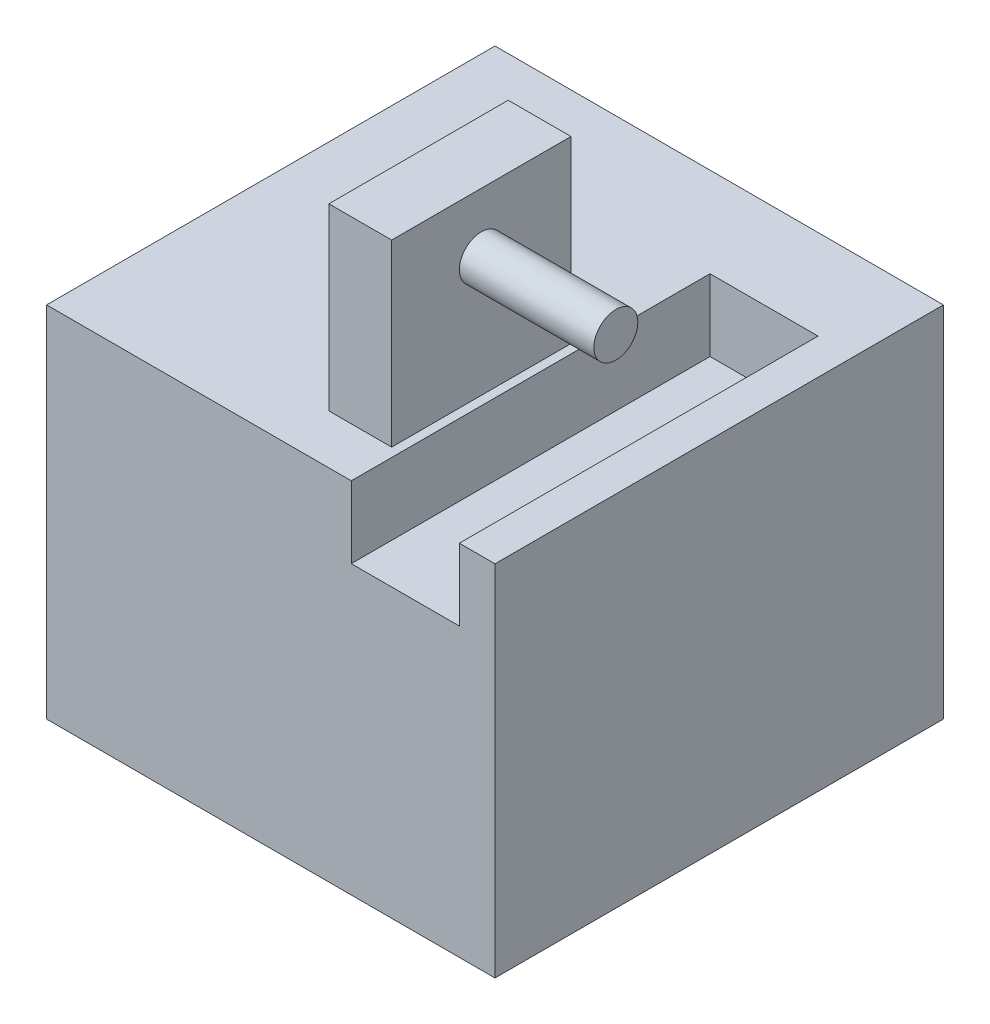
SolidWorks part; units mm, degrees
ref_plane "Front Plane" through (0, 0, 0) normal (0, 0, 1) x (1, 0, 0)
ref_plane "Top Plane" through (0, 0, 0) normal (0, 1, 0) x (1, 0, 0)
ref_plane "Right Plane" through (0, 0, 0) normal (1, 0, 0) x (0, 0, -1)
sketch "Sketch1" plane through (0, 0, 0) normal (0, 1, 0) x (1, 0, 0)
  line L1 (-40, 40) -> (40, 40)
  line L2 (-40, 40) -> (-40, -40)
  line L3 (-40, -40) -> (40, -40)
  line L4 (40, 40) -> (40, -40)
  line L5 (-40, 40) -> (40, -40) construction
  line L6 (-40, -40) -> (40, 40) construction
  point P0 (0, 0)
  dimension "D1" = 80
extrude "Boss-Extrude1" add sketch "Sketch1" along normal blind 40
sketch "Sketch2" plane through (0, 40, 0) normal (0, 1, 0) x (1, 0, 0)
  line L0 (-40, -40) -> (40, -40) construction
  line L1 (-6.025, -40) -> (6.025, -40)
  line L2 (-6.025, -40) -> (-6.025, 40)
  line L3 (-6.025, 40) -> (6.025, 40)
  line L4 (6.025, -40) -> (6.025, 40)
  line L5 (40, 40) -> (-40, 40) construction
  point P7 (0, 40)
  dimension "D1" = 12.05
extrude "Cut-Extrude1" cut sketch "Sketch2" against normal blind 8
sketch "Sketch3" plane through (0, 40, 0) normal (0, 1, 0) x (1, 0, 0)
  line L1 (-7.025, -14.5) -> (-14.025, -14.5)
  line L2 (-7.025, -14.5) -> (-7.025, -34.5)
  line L3 (-7.025, -34.5) -> (-14.025, -34.5)
  line L4 (-14.025, -14.5) -> (-14.025, -34.5)
  line L7 (-6.025, 40) -> (-6.025, -40) construction
  dimension "D1" = 20
  dimension "D2" = 7
  dimension "D3" = 14.5
  dimension "D4" = 1
extrude "Boss-Extrude2" add sketch "Sketch3" along normal blind 20
sketch "Sketch4" plane through (-7.025, 0, 0) normal (1, 0, 0) x (0, 0, -1)
  line L0 (-34.5, 40) -> (-14.5, 40) construction
  line L1 (-34.5, 60) -> (-14.5, 60) construction
  circle A0 centre (-24.5, 53.35) radius 2.45
  point P6 (-24.5, 60)
  dimension "D1" = 4.9
  dimension "D2" = 13.35
extrude "Boss-Extrude3" add sketch "Sketch4" along normal blind 15
sketch "Sketch6" plane through (0, 0, -40) normal (0, 0, -1) x (-1, 0, 0)
  line L1 (-40, 40) -> (40, 40)
  line L2 (-40, 40) -> (-40, 0)
  line L3 (-40, 0) -> (40, 0)
  line L4 (40, 40) -> (40, 0)
extrude "Cut-Extrude3" cut sketch "Sketch6" against normal blind 30
sketch "Sketch7" plane through (40, 0, 0) normal (1, 0, 0) x (0, 0, -1)
  line L1 (-40, 40) -> (10, 40)
  line L2 (-40, 40) -> (-40, 0)
  line L3 (-40, 0) -> (10, 0)
  line L4 (10, 40) -> (10, 0)
extrude "Cut-Extrude4" cut sketch "Sketch7" against normal blind 30
sketch "Sketch8" plane through (0, 32, 0) normal (0, 1, 0) x (1, 0, 0)
  line L0 (6.025, -40) -> (6.025, 10) construction
  line L1 (-6.025, 10) -> (6.025, 10)
  line L2 (-6.025, 10) -> (-6.025, 0)
  line L3 (-6.025, 0) -> (6.025, 0)
  line L4 (6.025, 10) -> (6.025, 0)
  dimension "D1" = 10
extrude "Boss-Extrude4" add sketch "Sketch8" along normal up to surface (8 mm away) up to face at (-10.525, 40, 24.5)
